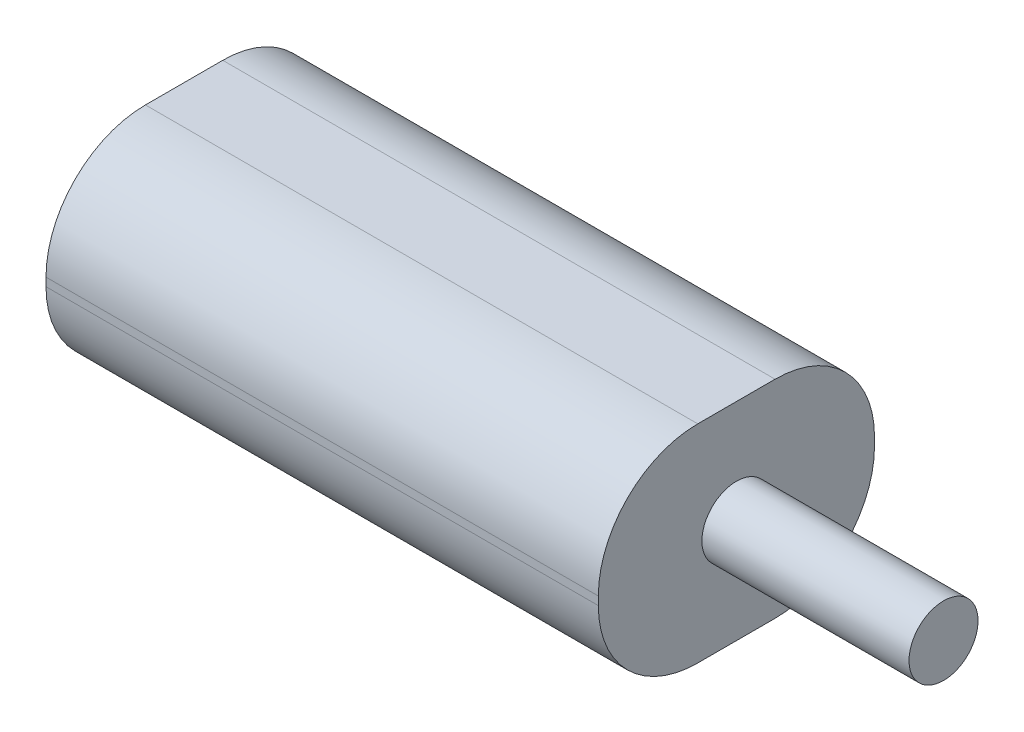
SolidWorks part; units mm, degrees
ref_plane "Front Plane" through (0, 0, 0) normal (0, 0, 1) x (1, 0, 0)
ref_plane "Top Plane" through (0, 0, 0) normal (0, 1, 0) x (1, 0, 0)
ref_plane "Right Plane" through (0, 0, 0) normal (1, 0, 0) x (0, 0, -1)
sketch "Sketch1" plane through (0, 0, 0) normal (0, 1, 0) x (1, 0, 0)
  line L1 (-12.7, 6.35) -> (12.7, 6.35)
  line L2 (-12.7, 6.35) -> (-12.7, -6.35)
  line L3 (-12.7, -6.35) -> (12.7, -6.35)
  line L4 (12.7, 6.35) -> (12.7, -6.35)
  dimension "D1" = 25.4
  dimension "D2" = 12.7
  dimension "D3" = 6.35
  dimension "D4" = 12.7
extrude "Boss-Extrude1" add sketch "Sketch1" along normal blind 9.525
sketch "Sketch2" plane through (12.7, 0, 0) normal (1, 0, 0) x (0, 0, -1)
  circle A0 centre (0, 4.7625) radius 1.5875
  dimension "D1" = 3.175
extrude "Boss-Extrude2" add sketch "Sketch2" along normal blind 9.525
fillet "Fillet1" radius 4.572 4 edges at (0, 9.525, -6.35) (0, 0, -6.35) (0, 0, 6.35) (0, 9.525, 6.35)
